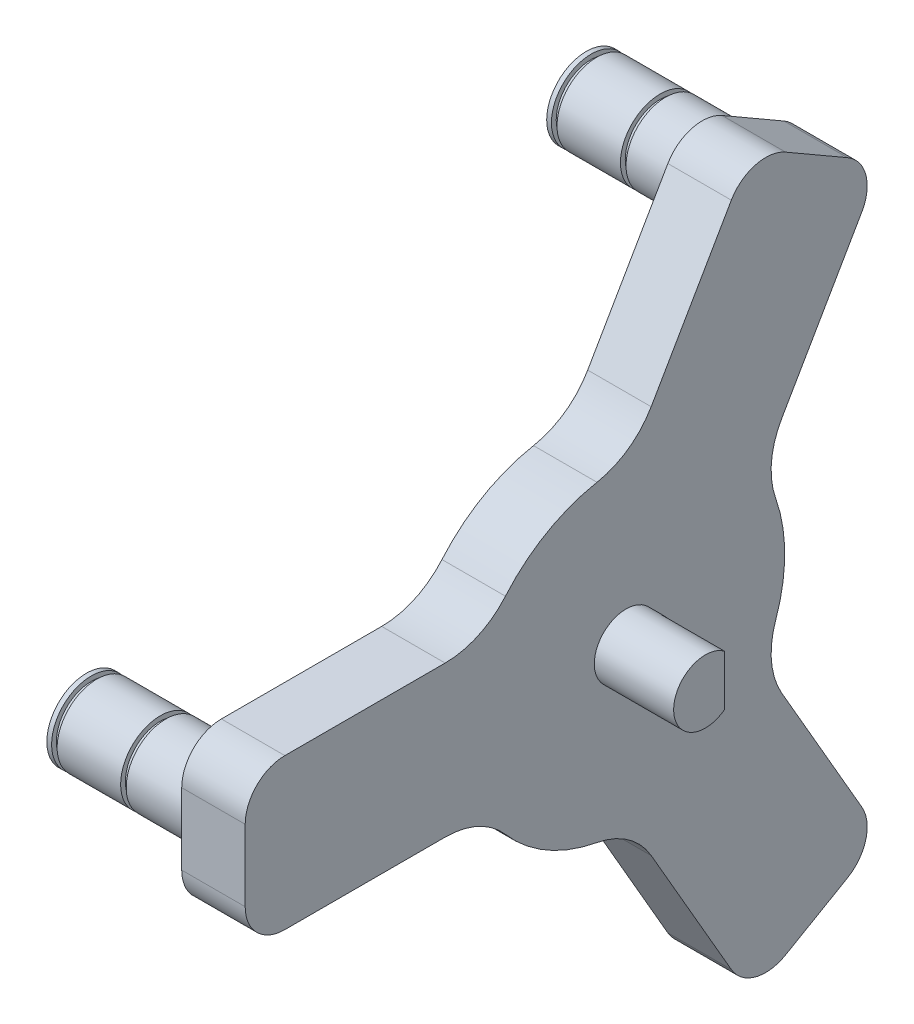
SolidWorks part; units mm, degrees
ref_plane "Front Plane" through (0, 0, 0) normal (1, 0, 0) x (0, 1, 0)
ref_plane "Top Plane" through (0, 0, 0) normal (0, 0, 1) x (0, 1, 0)
ref_plane "Right Plane" through (0, 0, 0) normal (0, 1, 0) x (-1, 0, 0)
sketch "Sketch1" plane through (0, 0, 0) normal (1, 0, 0) x (0, 1, 0)
  line L0 (0, 0) -> (0, 48) construction
  line L1 (46.3192, -15.7728) -> (19.9918, -0.5726) construction
  line L2 (36.8192, -32.2272) -> (10.4918, -17.0271) construction
  line L3 (-9.5, 48) -> (9.5, 48) construction
  line L4 (9.5, 48) -> (9.5, 17.5997) construction
  line L5 (-9.5, 48) -> (-9.5, 17.5997) construction
  line L6 (46.3192, -15.7728) -> (36.8192, -32.2272) construction
  line L7 (-36.8192, -32.2272) -> (-10.4918, -17.0271) construction
  line L8 (-46.3192, -15.7728) -> (-19.9918, -0.5726) construction
  line L9 (-36.8192, -32.2272) -> (-46.3192, -15.7728) construction
  line L10 (-19.9918, -0.5726) -> (-46.3192, -15.7728)
  line L11 (-46.3192, -15.7728) -> (-36.8192, -32.2272)
  line L12 (-36.8192, -32.2272) -> (-10.4918, -17.0271)
  line L13 (10.4918, -17.0271) -> (36.8192, -32.2272)
  line L14 (36.8192, -32.2272) -> (46.3192, -15.7728)
  line L15 (46.3192, -15.7728) -> (19.9918, -0.5726)
  line L16 (9.5, 17.5997) -> (9.5, 48)
  line L17 (9.5, 48) -> (-9.5, 48)
  line L18 (-9.5, 48) -> (-9.5, 17.5997)
  arc A0 (-9.5, 17.5997) -> (-19.9918, -0.5726) centre (0, 0) ccw construction
  arc A1 (19.9918, -0.5726) -> (9.5, 17.5997) centre (0, 0) ccw construction
  arc A2 (-10.4918, -17.0271) -> (10.4918, -17.0271) centre (0, 0) ccw construction
  arc A3 (-10.4918, -17.0271) -> (10.4918, -17.0271) centre (0, 0) ccw
  arc A4 (-10.4918, -17.0271) -> (10.4918, -17.0271) centre (0, 0) ccw construction
  arc A5 (-10.4918, -17.0271) -> (10.4918, -17.0271) centre (0, 0) ccw construction
  arc A6 (19.9918, -0.5726) -> (9.5, 17.5997) centre (0, 0) ccw construction
  arc A7 (19.9918, -0.5726) -> (9.5, 17.5997) centre (0, 0) ccw
  arc A8 (19.9918, -0.5726) -> (9.5, 17.5997) centre (0, 0) ccw construction
  arc A9 (-9.5, 17.5997) -> (-19.9918, -0.5726) centre (0, 0) ccw construction
  arc A10 (-9.5, 17.5997) -> (-19.9918, -0.5726) centre (0, 0) ccw construction
  arc A11 (-9.5, 17.5997) -> (-19.9918, -0.5726) centre (0, 0) ccw
  point P18 (0, 0)
  dimension "D4" = 40
  dimension "D1" = 19
  dimension "D2" = 3
  dimension "D3" = 48
extrude "Boss-Extrude2" add sketch "Sketch1" along normal blind 8
fillet "Fillet1" radius 10 6 edges at (4, 10.4918, -17.0271) (4, -10.4918, -17.0271) (4, -19.9918, -0.5726) (4, -9.5, 17.5997) (4, 19.9918, -0.5726) (4, 9.5, 17.5997)
fillet "Fillet3" radius 5 2 edges at (4, 9.5, 48) (4, -9.5, 48)
fillet "Fillet4" radius 5 4 edges at (4, 46.3192, -15.7728) (4, 36.8192, -32.2272) (4, -36.8192, -32.2272) (4, -46.3192, -15.7728)
sketch "Sketch2" plane through (0, 0, 0) normal (-1, 0, 0) x (0, -1, 0)
  line L0 (0, 0) -> (0, 42) construction
  line L1 (0, 0) -> (-36.3731, -21) construction
  line L2 (0, 0) -> (36.3731, -21) construction
  circle A0 centre (0, 42) radius 5
  circle A1 centre (-36.3731, -21) radius 5
  circle A2 centre (36.3731, -21) radius 5
  dimension "D1" = 10
  dimension "D2" = 42
sketch "Sketch3" plane through (0, 0, 0) normal (-1, 0, 0) x (0, -1, 0)
  circle A0 centre (0, 0) radius 5
  dimension "D1" = 10
extrude "Boss-Extrude3" add sketch "Sketch3" along normal blind 10
extrude "Boss-Extrude4" add sketch "Sketch2" along normal blind 18
sketch "Sketch4" plane through (8, 0, 0) normal (1, 0, 0) x (0, 1, 0)
  circle A0 centre (0, 0) radius 4
  dimension "D1" = 8
extrude "Boss-Extrude5" add sketch "Sketch4" along normal blind 10
sketch "Sketch5" plane through (18, 0, 0) normal (1, 0, 0) x (0, 1, 0)
  line L0 (-3.2, -2.4) -> (3.2, -2.4)
  circle A0 centre (0, 0) radius 4 construction
  circle A1 centre (0, 0) radius 4 construction
  arc A2 (-3.2, -2.4) -> (3.2, -2.4) centre (0, 0) ccw
  dimension "D1" = 6.4
extrude "Cut-Extrude1" cut sketch "Sketch5" against normal blind 8
sketch "Sketch7" plane through (0, 0, 0) normal (0, 1, 0) x (-1, 0, 0)
  line L0 (18, 47) -> (0, 47) construction
  line L6 (8.7, 46.4) -> (8, 46.4)
  line L12 (8.7, 46.4) -> (8.7, 47.6)
  line L13 (8.7, 47.6) -> (8, 47.6)
  line L14 (21.8155, 42) -> (-10.848, 42) construction
  line L15 (8, 46.4) -> (8, 47.6)
  line L16 (8.7, 46.4) -> (8, 47.6) construction
  line L17 (8.7, 47.6) -> (8, 46.4) construction
  line L18 (17.4, 46.4) -> (16.7, 46.4)
  line L19 (17.4, 46.4) -> (17.4, 47.6)
  line L20 (17.4, 47.6) -> (16.7, 47.6)
  line L21 (16.7, 46.4) -> (16.7, 47.6)
  line L22 (17.4, 46.4) -> (16.7, 47.6) construction
  line L23 (17.4, 47.6) -> (16.7, 46.4) construction
  line L25 (0, 37) -> (0, 47) construction
  point P0 (8.35, 47)
  point P7 (17.05, 47)
  dimension "D1" = 0.7
  dimension "D2" = 0.6
  dimension "D3" = 8
  dimension "D4" = 5
  dimension "D5" = 8
revolve "Cut-Revolve1" cut sketch "Sketch7" angle 360 about L14
pattern_circular "CirPattern1" count 3 every 120 about axis through (0, 0, 0) along (1, 0, 0) of "Cut-Revolve1"
